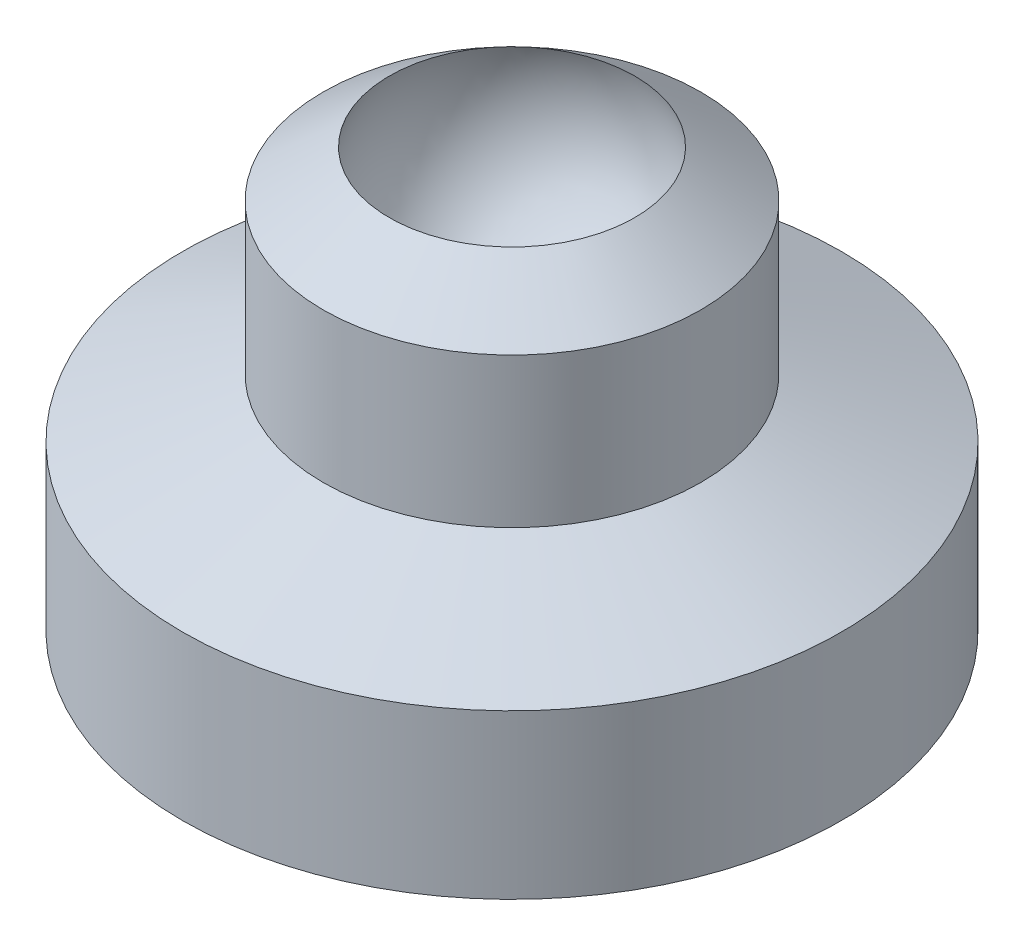
SolidWorks part; units mm, degrees
ref_plane "Front Plane" through (0, 0, 0) normal (0, 0, 1) x (1, 0, 0)
ref_plane "Top Plane" through (0, 0, 0) normal (0, 1, 0) x (1, 0, 0)
ref_plane "Right Plane" through (0, 0, 0) normal (1, 0, 0) x (0, 0, -1)
sketch "Sketch1" plane through (0, 0, 0) normal (1, 0, 0) x (0, 0, -1)
  line L0 (-345.4792, 0) -> (-395.3142, 0)
  line L1 (-395.3142, 0) -> (-395.3142, 24.6962)
  line L2 (-395.3142, 24.6962) -> (-374.0302, 33.6268)
  line L3 (-374.0302, 33.6268) -> (-374.0302, 56.2328)
  line L4 (-374.0302, 56.2328) -> (-364.0391, 63.3176)
  line L5 (-345.4792, 0) -> (-345.4792, 29.1615) construction
  line L6 (-345.4792, 36.3666) -> (-345.4792, 0)
  arc A0 (-364.0391, 63.3176) -> (-345.4792, 36.3666) centre (-345.4792, 56.2328) ccw
  dimension "D2" = 49.8349
revolve "Revolve1" add sketch "Sketch1" angle 360 about L5
move or copy body "Body-Move/Copy1" [suppressed] bodies to move or copy 101
